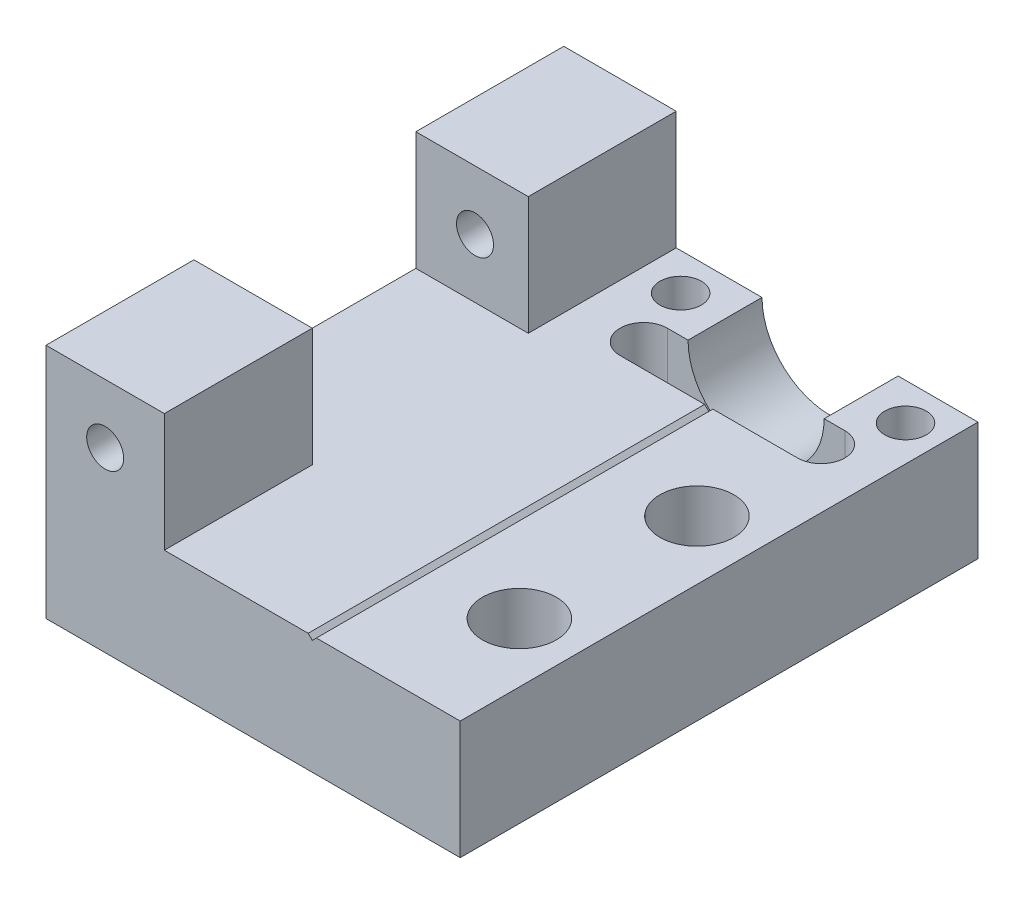
SolidWorks part; units mm, degrees
ref_plane "Front Plane" through (0, 0, 0) normal (0, 0, 1) x (1, 0, 0)
ref_plane "Top Plane" through (0, 0, 0) normal (0, 1, 0) x (1, 0, 0)
ref_plane "Right Plane" through (0, 0, 0) normal (1, 0, 0) x (0, 0, -1)
sketch "Sketch1" plane through (0, 0, 0) normal (0, 0, 1) x (1, 0, 0)
  line L0 (9.271, 5.08) -> (12.7, 5.08)
  line L1 (0, 0) -> (12.7, 0)
  line L2 (0, 0) -> (0, 5.08)
  line L3 (0, 5.08) -> (3.429, 5.08)
  line L4 (12.7, 0) -> (12.7, 5.08)
  arc A0 (3.429, 5.08) -> (9.271, 5.08) centre (6.35, 5.08) ccw
  dimension "D1" = 5.842
  dimension "D2" = 12.7
  dimension "D3" = 5.08
  dimension "D4" = 6.35
extrude "Boss-Extrude1" add sketch "Sketch1" along normal blind 3.175
sketch "Sketch3" plane through (0, 0, 0) normal (0, -1, 0) x (1, 0, 0)
  line L0 (0, 3.175) -> (12.7, 3.175)
  line L2 (12.7, 3.175) -> (12.7, 22.225)
  line L3 (12.7, 22.225) -> (0, 22.225)
  line L4 (0, 3.175) -> (0, 22.225)
  dimension "D1" = 19.05
extrude "Boss-Extrude2" add sketch "Sketch3" against normal blind 5.08
sketch "Sketch7" plane through (0, 5.08, 0) normal (0, 1, 0) x (1, 0, 0)
  line L0 (2.54, -4.191) -> (10.16, -4.191) construction
  line L1 (2.54, -3.175) -> (10.16, -3.175)
  line L2 (2.54, -5.207) -> (10.16, -5.207)
  line L8 (3.429, 0) -> (0, 0)
  line L9 (0, 0) -> (0, -22.225)
  line L10 (0, -22.225) -> (12.7, -22.225)
  line L11 (12.7, -22.225) -> (12.7, 0)
  line L12 (12.7, 0) -> (9.271, 0)
  line L13 (9.271, 0) -> (9.271, -3.175)
  line L14 (9.271, -3.175) -> (3.429, -3.175)
  line L15 (3.429, -3.175) -> (3.429, 0)
  line L16 (3.429, 0) -> (0, 0)
  line L17 (0, 0) -> (0, -22.225)
  line L18 (0, -22.225) -> (12.7, -22.225)
  line L19 (12.7, -22.225) -> (12.7, 0)
  line L20 (12.7, 0) -> (9.271, 0)
  line L21 (9.271, 0) -> (9.271, -3.175)
  line L22 (9.271, -3.175) -> (3.429, -3.175)
  line L23 (3.429, -3.175) -> (3.429, 0)
  arc A0 (2.54, -3.175) -> (2.54, -5.207) centre (2.54, -4.191) ccw
  arc A1 (10.16, -5.207) -> (10.16, -3.175) centre (10.16, -4.191) ccw
  point P6 (6.35, -4.191)
  dimension "D2" = 6.35
  dimension "D3" = 2.032
  dimension "D4" = 7.62
  dimension "D1" = 0
extrude "Cut-Extrude2" cut sketch "Sketch7" against normal through all contours A0 L2 A1 L1
sketch "Sketch6" plane through (0, 0, 22.225) normal (0, 0, 1) x (1, 0, 0)
  line L0 (6.1732, 5.08) -> (6.35, 4.9032)
  line L1 (12.7, 5.08) -> (0, 5.08) construction
  line L2 (6.35, 4.9032) -> (6.5268, 5.08)
  line L4 (6.5268, 5.08) -> (6.1732, 5.08)
  circle A0 centre (6.35, 5.08) radius 0.125 construction
  dimension "D2" = 0.25
  dimension "D1" = 45
extrude "Cut-Extrude3" cut sketch "Sketch6" against normal through all contours L2 L4 L0
hole_wizard "#2-56 Tapped Hole1" positions "3DSketch1" profile "Sketch8" tap size "#2-56" standard "ANSI Inch" end condition up to next
sketch3d "3DSketch1"
  line L0 (12.7, 5.08, 0) -> (9.271, 5.08, 0) construction
  line L1 (12.7, 5.08, 22.225) -> (12.7, 5.08, 0) construction
  line L2 (0, 5.08, 22.225) -> (0, 5.08, 0) construction
  point P0 (11.176, 5.08, 1.5875)
  point P7 (1.524, 5.08, 1.5875)
  dimension "D1" = 1.5875
  dimension "D2" = 1.524
  dimension "D3" = 1.524
sketch "Sketch8" plane through (11.176, 5.08, 1.5875) normal (1, 0, 0) x (0, 0, 1)
  line L0 (0, 0) -> (0, 5.08)
  line L1 (0, 5.08) -> (0.889, 5.08)
  line L2 (0.889, 5.08) -> (0.889, 0)
  line L5 (0.889, 0) -> (0, 0)
  line L11 (0, -6.35) -> (0, 107.95) construction
  dimension "Thru Tap Drill Dia." = 1.778
  dimension "Thru Tap Drill Depth" = 5.08
cosmetic thread "Hole Thread1" parameters "D2"=2.1844
cosmetic thread "Hole Thread2" parameters "D2"=2.1844
sketch "Sketch9" plane through (0, 0, 0) normal (-1, 0, 0) x (0, 0, 1)
  line L0 (22.225, 0) -> (0, 0) construction
  line L2 (0, 5.08) -> (0, 0)
  line L6 (22.225, 5.08) -> (0, 5.08)
  line L7 (22.225, 5.08) -> (22.225, 0)
  line L8 (22.225, 0) -> (0, 0)
extrude "Boss-Extrude3" add sketch "Sketch9" along normal blind 5.08
sketch "Sketch12" plane through (0, 5.08, 0) normal (0, 1, 0) x (1, 0, 0)
  line L0 (12.7, -22.225) -> (12.7, 0) construction
  line L2 (12.7, -22.225) -> (6.5268, -22.225) construction
  circle A0 centre (10.16, -17.145) radius 1.5875
  circle A1 centre (10.16, -9.525) radius 1.5875
  dimension "D1" = 3.175
  dimension "D2" = 2.54
  dimension "D3" = 7.62
  dimension "D4" = 5.08
extrude "Cut-Extrude4" cut sketch "Sketch12" against normal blind 3.302
sketch "Sketch13" plane through (0, 5.08, 0) normal (0, 1, 0) x (1, 0, 0)
  line L1 (-5.08, 0) -> (-0.254, 0)
  line L2 (-5.08, 0) -> (-5.08, -6.35)
  line L3 (-5.08, -6.35) -> (-0.254, -6.35)
  line L4 (-0.254, 0) -> (-0.254, -6.35)
  line L5 (-5.08, -22.225) -> (0, -22.225)
  line L6 (-5.08, -22.225) -> (-5.08, -15.875)
  line L7 (-5.08, -15.875) -> (0, -15.875)
  line L8 (0, -22.225) -> (0, -15.875)
  dimension "D1" = 5.08
  dimension "D2" = 6.35
  dimension "D3" = 6.35
  dimension "D4" = 0.254
extrude "Boss-Extrude4" add sketch "Sketch13" along normal blind 5.08
hole_wizard "1/16 (0.0625) Diameter Hole1" positions "Sketch10" profile "Sketch11" hole size "1/16" standard "ANSI Inch" end condition through all
sketch "Sketch10" plane through (0, 0, 22.225) normal (0, 0, 1) x (1, 0, 0)
  line L0 (-5.08, 0) -> (-5.08, 10.16) construction
  line L3 (-5.08, 10.16) -> (0, 10.16) construction
  point P0 (-2.54, 7.62)
  dimension "D1" = 2.54
  dimension "D2" = 2.54
sketch "Sketch11" plane through (-2.54, 7.62, 22.225) normal (1, 0, 0) x (0, -1, 0)
  line L0 (0, 0) -> (0, 22.225)
  line L1 (0, 22.225) -> (0.7937, 22.225)
  line L2 (0.7937, 22.225) -> (0.7937, 0)
  line L5 (0.7937, 0) -> (0, 0)
  line L11 (0, -6.35) -> (0, 107.95) construction
  dimension "Thru Hole Dia." = 1.5875
  dimension "Thru Hole Depth" = 22.225
hole_wizard "3/64 (0.04688) Diameter Hole1" positions "3DSketch2" profile "Sketch15" hole size "3/64" standard "ANSI Inch" end condition through all
sketch3d "3DSketch2"
  line L0 (10.16, 1.778, 17.145) -> (10.16, 5.08, 17.145) construction
  line L1 (10.16, 1.778, 9.525) -> (10.16, 5.08, 9.525) construction
  point P0 (10.16, 5.08, 17.145)
  point P4 (10.16, 1.778, 9.525)
sketch "Sketch15" plane through (10.16, 5.08, 17.145) normal (1, 0, 0) x (0, 0, 1)
  line L0 (0, 0) -> (0, 5.08)
  line L1 (0, 5.08) -> (0.5954, 5.08)
  line L2 (0.5954, 5.08) -> (0.5954, 0)
  line L5 (0.5954, 0) -> (0, 0)
  line L11 (0, -6.35) -> (0, 107.95) construction
  dimension "Thru Hole Dia." = 1.1908
  dimension "Thru Hole Depth" = 5.08
